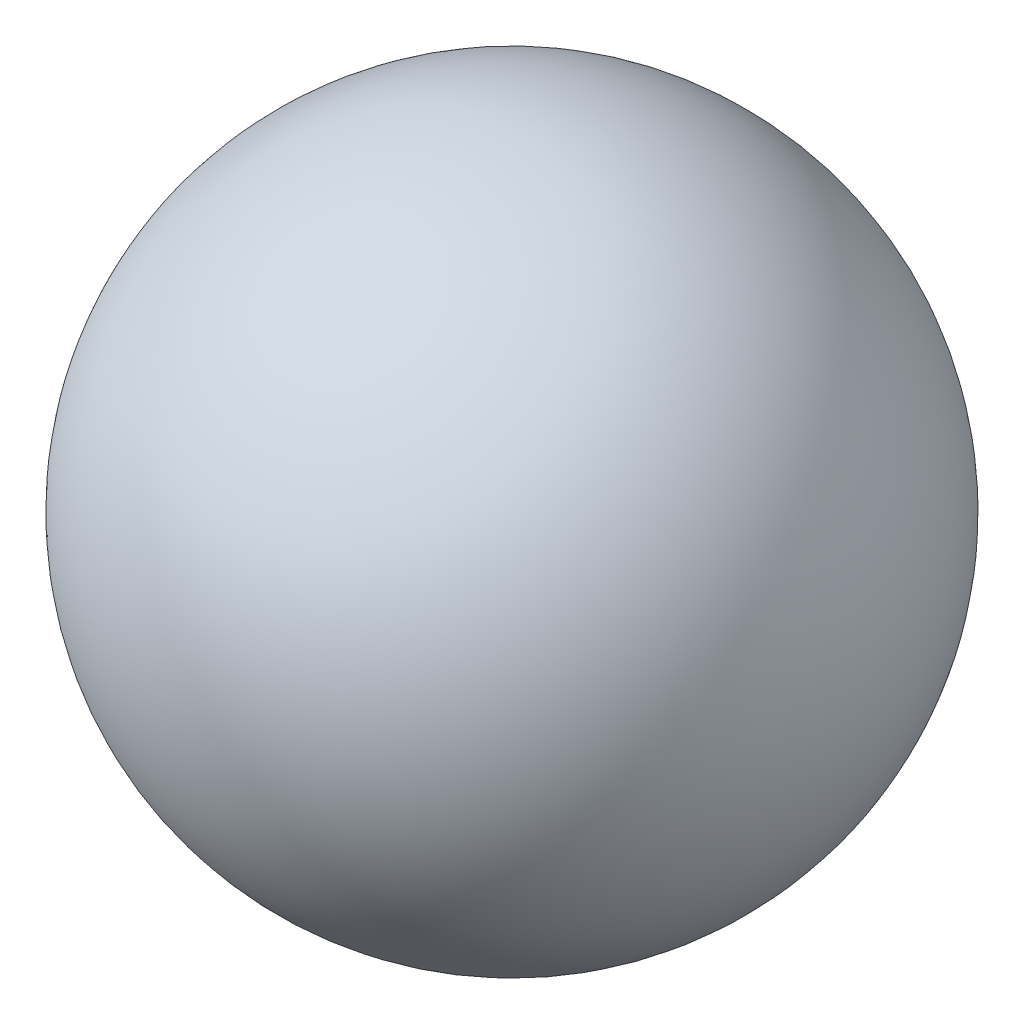
SolidWorks part; units mm, degrees
ref_plane "Front Plane" through (0, 0, 0) normal (0, 0, 1) x (1, 0, 0)
ref_plane "Top Plane" through (0, 0, 0) normal (0, 1, 0) x (1, 0, 0)
ref_plane "Right Plane" through (0, 0, 0) normal (1, 0, 0) x (0, 0, -1)
sketch "Sketch1" plane through (0, 0, 0) normal (0, 0, 1) x (1, 0, 0)
  line L0 (-111.7377, 0) -> (-87.7377, 0)
  arc A0 (-87.7377, 0) -> (-111.7377, 0) centre (-99.7377, 0) cw
  point P4 (0, 0)
  dimension "D1" = 24
revolve "Revolve1" add sketch "Sketch1" angle 360 about L0
